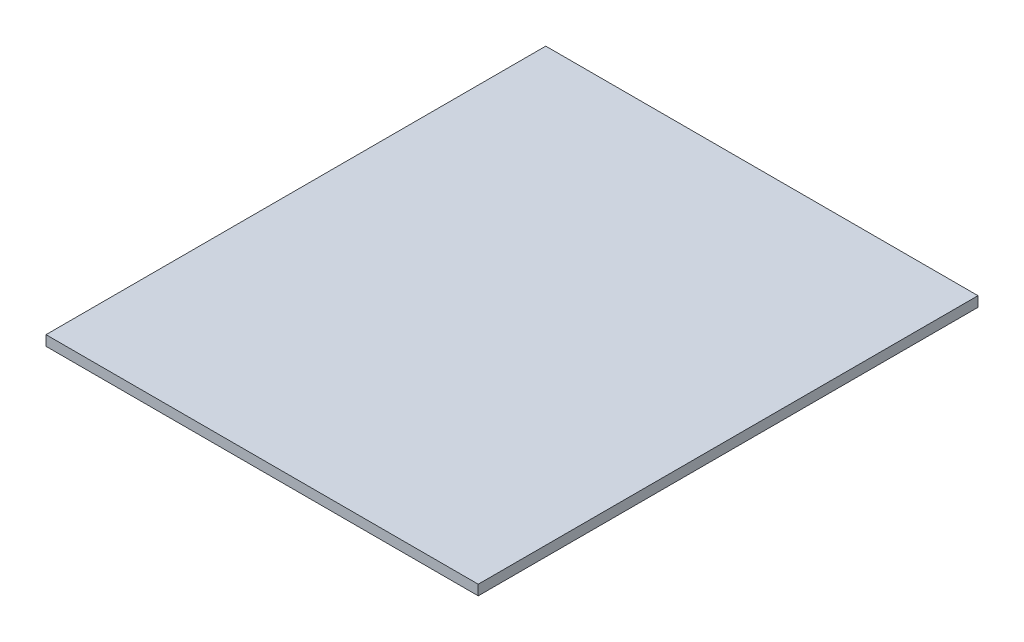
SolidWorks part; units mm, degrees
ref_plane "Front Plane" through (0, 0, 0) normal (0, 0, 1) x (1, 0, 0)
ref_plane "Top Plane" through (0, 0, 0) normal (0, 1, 0) x (1, 0, 0)
ref_plane "Right Plane" through (0, 0, 0) normal (1, 0, 0) x (0, 0, -1)
sketch "Sketch1" plane through (0, 0, 0) normal (0, 1, 0) x (1, 0, 0)
  line L1 (-32, 37) -> (32, 37)
  line L2 (-32, 37) -> (-32, -37)
  line L3 (-32, -37) -> (32, -37)
  line L4 (32, 37) -> (32, -37)
  line L5 (-32, 37) -> (32, -37) construction
  line L6 (-32, -37) -> (32, 37) construction
  point P0 (0, 0)
  dimension "D1" = 64
  dimension "D2" = 74
extrude "Boss-Extrude1" add sketch "Sketch1" along normal blind 1.5
